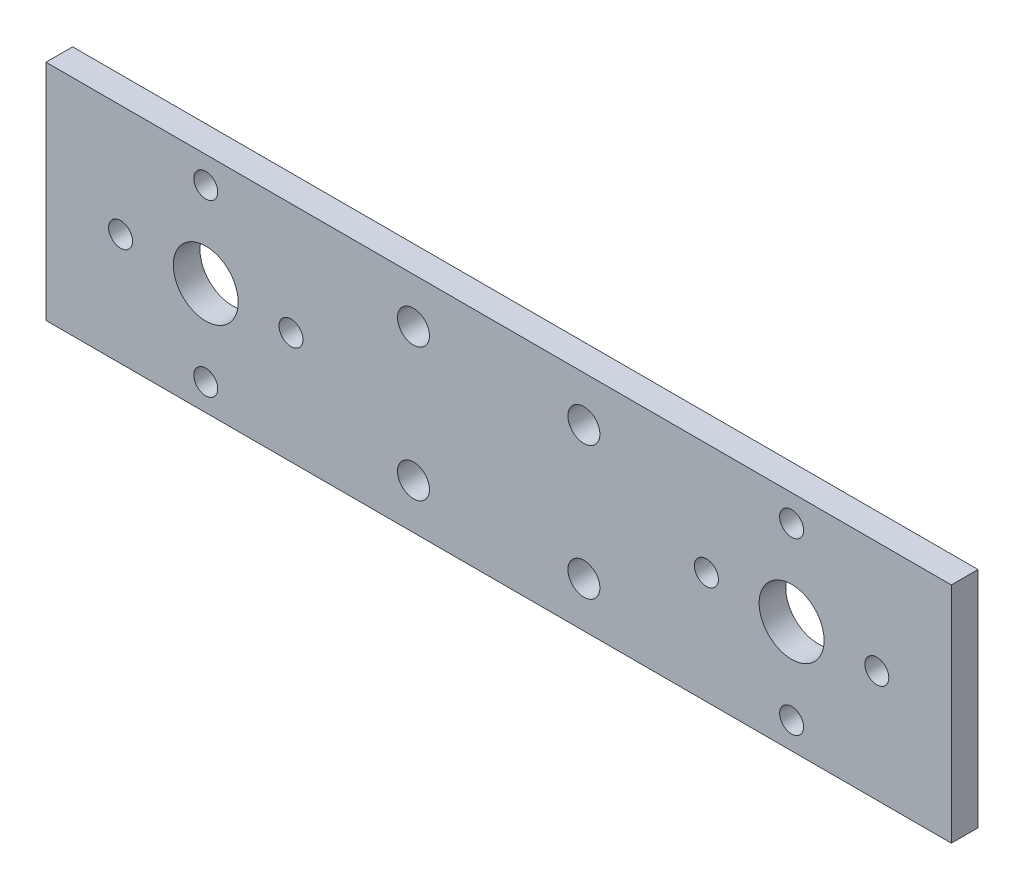
SolidWorks part; units mm, degrees
ref_plane "Front Plane" through (0, 0, 0) normal (0, 0, 1) x (1, 0, 0)
ref_plane "Top Plane" through (0, 0, 0) normal (0, 1, 0) x (1, 0, 0)
ref_plane "Right Plane" through (0, 0, 0) normal (1, 0, 0) x (0, 0, -1)
sketch "Sketch1" plane through (0, 0, 0) normal (0, 0, 1) x (1, 0, 0)
  line L1 (-85, 21) -> (85, 21)
  line L2 (-85, 21) -> (-85, -21)
  line L3 (-85, -21) -> (85, -21)
  line L4 (85, 21) -> (85, -21)
  line L5 (-85, 21) -> (85, -21) construction
  line L6 (-85, -21) -> (85, 21) construction
  point P0 (0, 0)
  dimension "D1" = 170
  dimension "D2" = 42
extrude "Boss-Extrude1" add sketch "Sketch1" along normal blind 5
sketch "Sketch2" plane through (0, 0, 5) normal (0, 0, 1) x (1, 0, 0)
  line L0 (0, 0) -> (-55, 0) construction
  circle A0 centre (-55, 0) radius 6.1
  circle A1 centre (55, 0) radius 6.1
  point P9 (0, 0)
  dimension "D2" = 12.2
  dimension "D4" = 12.2
  dimension "D1" = 55
  dimension "D3" = 2
extrude "Cut-Extrude1" cut sketch "Sketch2" against normal through all both and the other way through all
sketch "Sketch3" plane through (0, 0, 5) normal (0, 0, 1) x (1, 0, 0)
  line L0 (16, 12.5) -> (-16, -12.5) construction
  line L1 (-16, 12.5) -> (16, -12.5) construction
  circle A0 centre (-16, -12.5) radius 3
  circle A1 centre (-16, 12.5) radius 3
  circle A2 centre (16, 12.5) radius 3
  circle A3 centre (16, -12.5) radius 3
  point P0 (0, 0)
  dimension "D2" = 6
  dimension "D1" = 25
extrude "Cut-Extrude2" cut sketch "Sketch3" against normal through all both
sketch "Sketch4" plane through (0, 0, 5) normal (0, 0, 1) x (1, 0, 0)
  circle A1 centre (-71, 0) radius 2.25
  circle A2 centre (-55, 16) radius 2.25
  circle A3 centre (-39, 0) radius 2.25
  circle A4 centre (-55, -16) radius 2.25
  circle A6 centre (39, 0) radius 2.25
  circle A7 centre (55, 16) radius 2.25
  circle A8 centre (71, 0) radius 2.25
  circle A9 centre (55, -16) radius 2.25
  point P13 (-55, 0)
  point P22 (55, 0)
  dimension "D2" = 4.5
  dimension "D4" = 4.5
  dimension "D3" = 4
extrude "Cut-Extrude3" cut sketch "Sketch4" against normal through all
